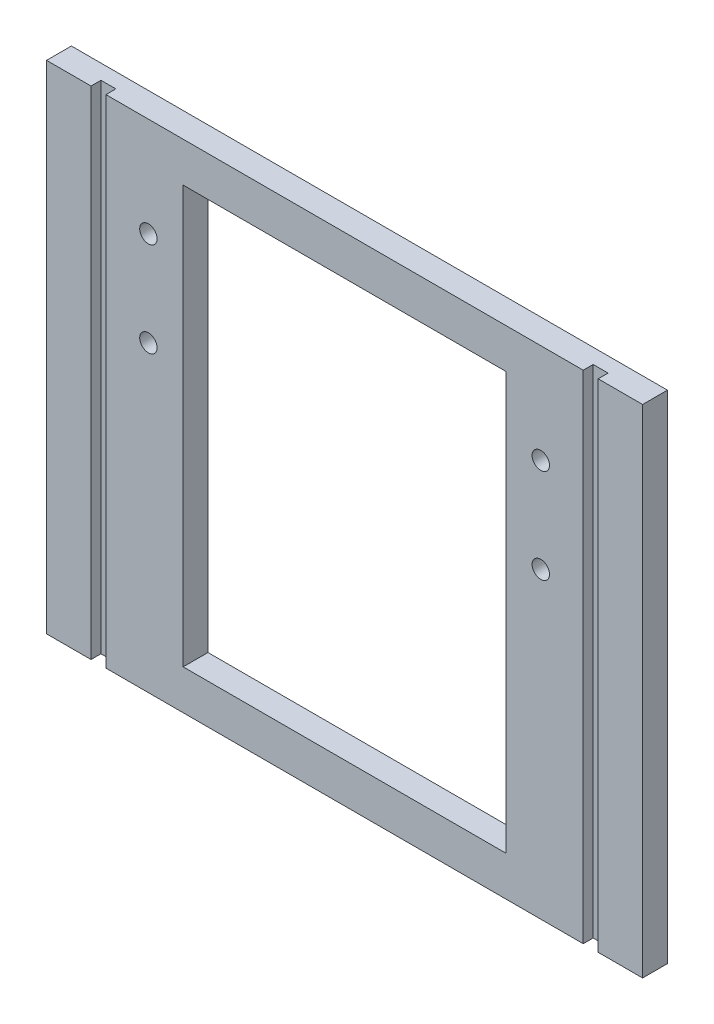
SolidWorks part; units mm, degrees
ref_plane "前视基准面" through (0, 0, 0) normal (0, 0, 1) x (1, 0, 0)
ref_plane "上视基准面" through (0, 0, 0) normal (0, 1, 0) x (1, 0, 0)
ref_plane "右视基准面" through (0, 0, 0) normal (1, 0, 0) x (0, 0, -1)
other "Configuration Table"
sketch "草图1" plane through (0, 0, 0) normal (0, 0, 1) x (1, 0, 0)
  line L0 (0, 70.5) -> (120, 70.5) construction
  line L1 (0, 0) -> (120, 0)
  line L2 (0, 0) -> (0, 100)
  line L3 (0, 100) -> (120, 100)
  line L4 (120, 0) -> (120, 100)
  line L5 (20.5, 80) -> (99.5, 80) construction
  line L7 (27.5, 92) -> (92.5, 92)
  line L8 (27.5, 92) -> (27.5, 8)
  line L9 (27.5, 8) -> (92.5, 8)
  line L10 (92.5, 92) -> (92.5, 8)
  circle A0 centre (20.5, 80) radius 1.75
  circle A1 centre (20.5, 61) radius 1.75
  circle A2 centre (99.5, 80) radius 1.75
  circle A3 centre (99.5, 61) radius 1.75
  point P15 (60, 100)
  point P16 (60, 80)
  dimension "D4" = 3.5
  dimension "D1" = 120
  dimension "D2" = 100
  dimension "D3" = 70.5
  dimension "D5" = 79
  dimension "D6" = 9.5
  dimension "D7" = 9.5
  dimension "D8" = 8
  dimension "D9" = 8
  dimension "D10" = 7
  dimension "D11" = 7
extrude "凸台-拉伸1" add sketch "草图1" along normal blind 5
sketch "草图2" plane through (0, 0, 5) normal (0, 0, 1) x (1, 0, 0)
  line L0 (120, 100) -> (0, 100) construction
  line L1 (8.95, 100) -> (11.95, 100)
  line L2 (8.95, 100) -> (8.95, 0)
  line L3 (8.95, 0) -> (11.95, 0)
  line L4 (11.95, 100) -> (11.95, 0)
  line L5 (0, 0) -> (120, 0) construction
  line L6 (120, 0) -> (120, 100) construction
  line L7 (108.05, 100) -> (111.05, 100)
  line L8 (108.05, 100) -> (108.05, 0)
  line L9 (108.05, 0) -> (111.05, 0)
  line L10 (111.05, 100) -> (111.05, 0)
  line L11 (0, 100) -> (0, 0) construction
  dimension "D1" = 3
  dimension "D2" = 3
  dimension "D3" = 8.95
  dimension "D4" = 8.95
extrude "切除-拉伸1" cut sketch "草图2" against normal blind 2
